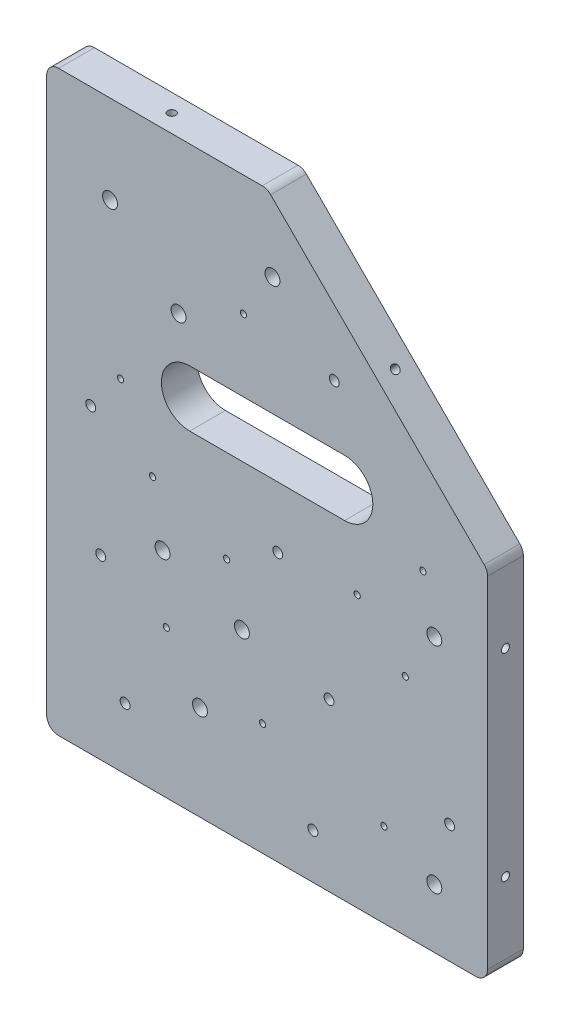
SolidWorks part; units mm, degrees
material "1060 Alloy"
ref_plane "Front Plane" through (0, 0, 0) normal (0, 0, 1) x (1, 0, 0)
ref_plane "Top Plane" through (0, 0, 0) normal (0, 1, 0) x (1, 0, 0)
ref_plane "Right Plane" through (0, 0, 0) normal (1, 0, 0) x (0, 0, -1)
sketch "Sketch1" plane through (0, 0, 0) normal (0, 0, 1) x (1, 0, 0)
  line L1 (0, 0) -> (370, 0)
  line L2 (0, 0) -> (0, 300)
  line L4 (370, 0) -> (370, 300)
  line L5 (185, 485) -> (370, 300)
  line L6 (120, 300) -> (250, 300) construction
  line L9 (185, 485) -> (185, 0) construction
  line L12 (120, 323.7101) -> (250, 323.7101)
  line L13 (120, 276.2899) -> (250, 276.2899)
  line L14 (185, 485) -> (0, 485)
  line L15 (0, 485) -> (0, 300)
  arc A4 (120, 323.7101) -> (120, 276.2899) centre (120, 300) ccw
  arc A5 (250, 276.2899) -> (250, 323.7101) centre (250, 300) ccw
  point P8 (185, 300)
  dimension "D1" = 370
  dimension "D2" = 300
  dimension "D3" = 300
extrude "Boss-Extrude2" add sketch "Sketch1" along normal blind 30
fillet "Fillet2" radius 10 2 edges at (0, 0, 15) (370, 0, 15)
fillet "Fillet3" radius 10 3 edges at (370, 300, 15) (0, 485, 15) (185, 485, 15)
sketch "Sketch6" plane through (0, 0, 30) normal (0, 0, 1) x (1, 0, 0)
  point P0 (300.971, 188.5529)
  point P2 (181.1557, 94.3665)
  point P4 (100.4245, 123.8398)
  point P6 (151.0416, 198.8045)
  point P8 (260.6054, 227.637)
  point P10 (283.0307, 70.6597)
  point P12 (88.8914, 227.637)
  point P14 (165.1376, 383.9736)
  point P16 (315.7076, 272.4877)
  point P18 (61.981, 285.3022)
  point P23 (88.8914, 227.637)
hole_wizard "Tap Drill for M5 Helicoil1" positions "Sketch6" profile "Sketch5" hole size "M5x0.8" standard "DIN" end condition through all
sketch "Sketch5" plane through (300.971, 188.5529, 30) normal (1, 0, 0) x (0, -1, 0)
  line L0 (0, 0) -> (0, 30)
  line L1 (0, 30) -> (2.6, 30)
  line L2 (2.6, 30) -> (2.6, 0)
  line L5 (2.6, 0) -> (0, 0)
  line L11 (0, -6.35) -> (0, 107.95) construction
  dimension "Thru Hole Dia." = 5.2
  dimension "Thru Hole Depth" = 30
sketch "Sketch9" plane through (0, 0, 30) normal (0, 0, 1) x (1, 0, 0)
  point P0 (65.8254, 51.438)
  point P2 (45.3222, 148.828)
  point P4 (236.8986, 139.8579)
  point P6 (241.3837, 373.722)
  point P8 (338.133, 99.4923)
  point P10 (223.4434, 37.9828)
  point P12 (193.9701, 225.0741)
  point P14 (36.9928, 253.266)
hole_wizard "Tap Drill for M8 Helicoil4" positions "Sketch9" profile "Sketch8" hole size "M8x1.25" standard "DIN" end condition through all
sketch "Sketch8" plane through (65.8254, 51.438, 30) normal (1, 0, 0) x (0, -1, 0)
  line L0 (0, 0) -> (0, 30)
  line L1 (0, 30) -> (4.15, 30)
  line L2 (4.15, 30) -> (4.15, 0)
  line L5 (4.15, 0) -> (0, 0)
  line L11 (0, -6.35) -> (0, 107.95) construction
  dimension "Thru Hole Dia." = 8.3
  dimension "Thru Hole Depth" = 30
sketch "Sketch12" plane through (0, 0, 30) normal (0, 0, 1) x (1, 0, 0)
  point P0 (163.8561, 153.9538)
  point P2 (325.3185, 49.5614)
  point P4 (128.6163, 79.6298)
  point P6 (189.4851, 423.0578)
  point P8 (110.676, 357.0632)
  point P10 (97.2208, 178.3013)
  point P12 (325.3185, 229.5592)
  point P13 (53.1905, 410.8867)
hole_wizard "Tap Drill for M12 Helicoil1" positions "Sketch12" profile "Sketch11" hole size "M12x1.75" standard "DIN" end condition through all
sketch "Sketch11" plane through (163.8561, 153.9538, 30) normal (1, 0, 0) x (0, -1, 0)
  line L0 (0, 0) -> (0, 30)
  line L1 (0, 30) -> (6.25, 30)
  line L2 (6.25, 30) -> (6.25, 0)
  line L5 (6.25, 0) -> (0, 0)
  line L11 (0, -6.35) -> (0, 107.95) construction
  dimension "Thru Hole Dia." = 12.5
  dimension "Thru Hole Depth" = 30
sketch "Sketch14" plane through (0, 0, 0) normal (0, -1, 0) x (-1, 0, 0)
  line L0 (-10, -15) -> (-65, -15) construction
  line L1 (-10, -30) -> (-10, 0) construction
  line L2 (-360, -15) -> (-315, -15) construction
  line L3 (-360, 0) -> (-360, -30) construction
  point P1 (-65, -15)
  point P5 (-315, -15)
  point P14 (-315, -15)
  point P16 (-65, -15)
  dimension "D1" = 55
  dimension "D2" = 45
hole_wizard "Tap Drill for M8 Tap1" positions "Sketch14" profile "Sketch17" hole size "M8" standard "DIN"
sketch "Sketch17" plane through (65, 0, 15) normal (1, 0, 0) x (0, 0, -1)
  line L0 (0, 0) -> (0, 27.0429)
  line L1 (0, 27.0429) -> (3.4, 25)
  line L2 (3.4, 25) -> (3.4, 0)
  line L5 (3.4, 0) -> (0, 0)
  line L10 (0, 27.0429) -> (-3.4, 25) construction
  line L11 (0, -6.35) -> (0, 107.95) construction
  dimension "Hole Dia." = 6.8
  dimension "Hole Depth" = 25
  dimension "Drill Angle" = 118
cosmetic thread "Cosmetic Thread11" parameters "D2"=8
cosmetic thread "Cosmetic Thread12" parameters "D2"=8
sketch "Sketch36" plane through (335, 335, 0) normal (0.7071, 0.7071, 0) x (0.7071, -0.7071, 0)
  line L0 (-207.9899, -15) -> (45.3553, -15) construction
  line L1 (-207.9899, 0) -> (-207.9899, -30) construction
  line L2 (45.3553, -30) -> (45.3553, 0) construction
  point P12 (-81.3173, -15)
hole_wizard "Tap Drill for M8 Tap2" positions "Sketch36" profile "Sketch37" hole size "M8" standard "DIN"
sketch "Sketch37" plane through (277.5, 392.5, 15) normal (0, 0, 1) x (-0.7071, 0.7071, 0)
  line L0 (0, 0) -> (0, 27.0429)
  line L1 (0, 27.0429) -> (3.4, 25)
  line L2 (3.4, 25) -> (3.4, 0)
  line L5 (3.4, 0) -> (0, 0)
  line L10 (0, 27.0429) -> (-3.4, 25) construction
  line L11 (0, -6.35) -> (0, 107.95) construction
  dimension "Hole Dia." = 6.8
  dimension "Hole Depth" = 25
  dimension "Drill Angle" = 118
cosmetic thread "Cosmetic Thread1" parameters "D2"=8
sketch "Sketch38" plane through (0, 485, 0) normal (0, 1, 0) x (1, 0, 0)
  line L0 (10, -15) -> (90, -15) construction
  line L1 (10, 0) -> (10, -30) construction
  point P1 (90, -15)
  point P9 (90, -15)
  dimension "D1" = 80
hole_wizard "Tap Drill for M8 Tap4" positions "Sketch38" profile "Sketch39" hole size "M8" standard "DIN"
sketch "Sketch39" plane through (90, 485, 15) normal (1, 0, 0) x (0, 0, 1)
  line L0 (0, 0) -> (0, 27.0429)
  line L1 (0, 27.0429) -> (3.4, 25)
  line L2 (3.4, 25) -> (3.4, 0)
  line L5 (3.4, 0) -> (0, 0)
  line L10 (0, 27.0429) -> (-3.4, 25) construction
  line L11 (0, -6.35) -> (0, 107.95) construction
  dimension "Hole Dia." = 6.8
  dimension "Hole Depth" = 25
  dimension "Drill Angle" = 118
cosmetic thread "Cosmetic Thread9" parameters "D2"=8
sketch "Sketch40" plane through (370, 0, 0) normal (1, 0, 0) x (0, 0, -1)
  line L0 (-15, 10) -> (-15, 70) construction
  line L1 (-30, 10) -> (0, 10) construction
  line L2 (-15, 295.8579) -> (-15, 235.8579) construction
  line L3 (0, 295.8579) -> (-30, 295.8579) construction
  point P1 (-15, 70)
  point P5 (-15, 235.8579)
  point P14 (-15, 70)
  point P16 (-15, 235.8579)
  dimension "D1" = 60
  dimension "D2" = 60
hole_wizard "Tap Drill for M8 Tap5" positions "Sketch40" profile "Sketch41" hole size "M8" standard "DIN"
sketch "Sketch41" plane through (370, 235.8579, 15) normal (0, 1, 0) x (0, 0, -1)
  line L0 (0, 0) -> (0, 27.0429)
  line L1 (0, 27.0429) -> (3.4, 25)
  line L2 (3.4, 25) -> (3.4, 0)
  line L5 (3.4, 0) -> (0, 0)
  line L10 (0, 27.0429) -> (-3.4, 25) construction
  line L11 (0, -6.35) -> (0, 107.95) construction
  dimension "Hole Dia." = 6.8
  dimension "Hole Depth" = 25
  dimension "Drill Angle" = 118
cosmetic thread "Cosmetic Thread8" parameters "D2"=8
cosmetic thread "Cosmetic Thread10" parameters "D2"=8
